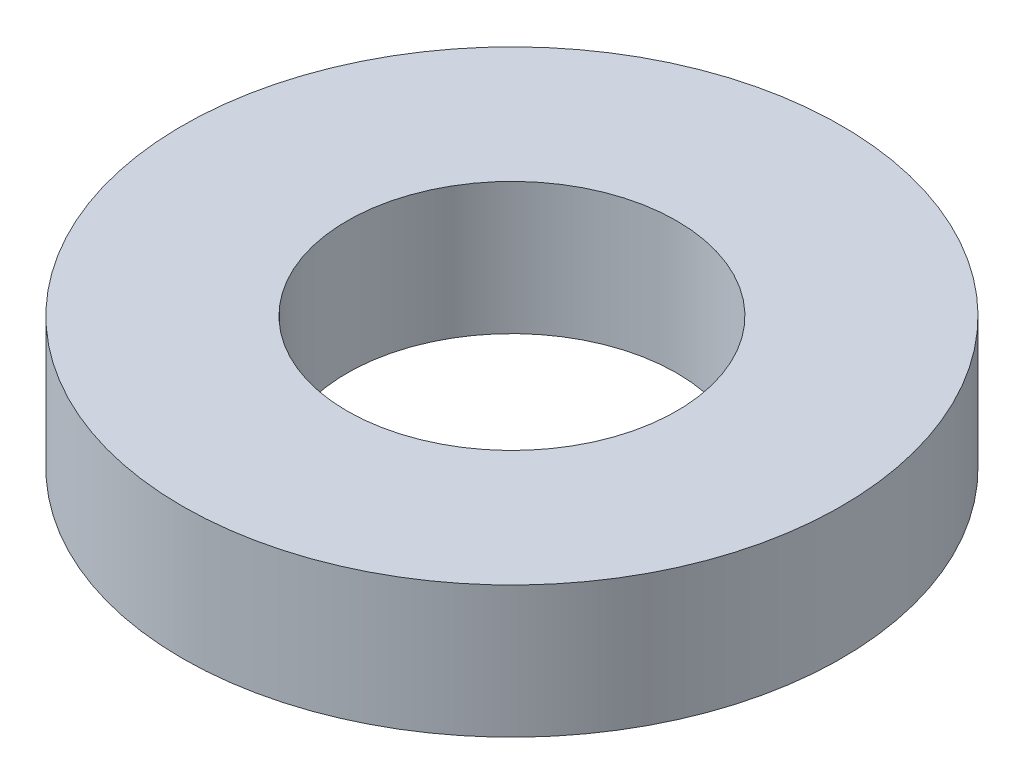
SolidWorks part; units mm, degrees
ref_plane "前视基准面" through (0, 0, 0) normal (0, 0, 1) x (1, 0, 0)
ref_plane "上视基准面" through (0, 0, 0) normal (0, 1, 0) x (1, 0, 0)
ref_plane "右视基准面" through (0, 0, 0) normal (1, 0, 0) x (0, 0, -1)
other "Configuration Table"
sketch "草图1" plane through (0, 0, 0) normal (0, 1, 0) x (1, 0, 0)
  circle A0 centre (0, 0) radius 2.5
  circle A1 centre (0, 0) radius 5
  dimension "D1" = 5
  dimension "D2" = 10
extrude "凸台-拉伸1" add sketch "草图1" along normal blind 2
